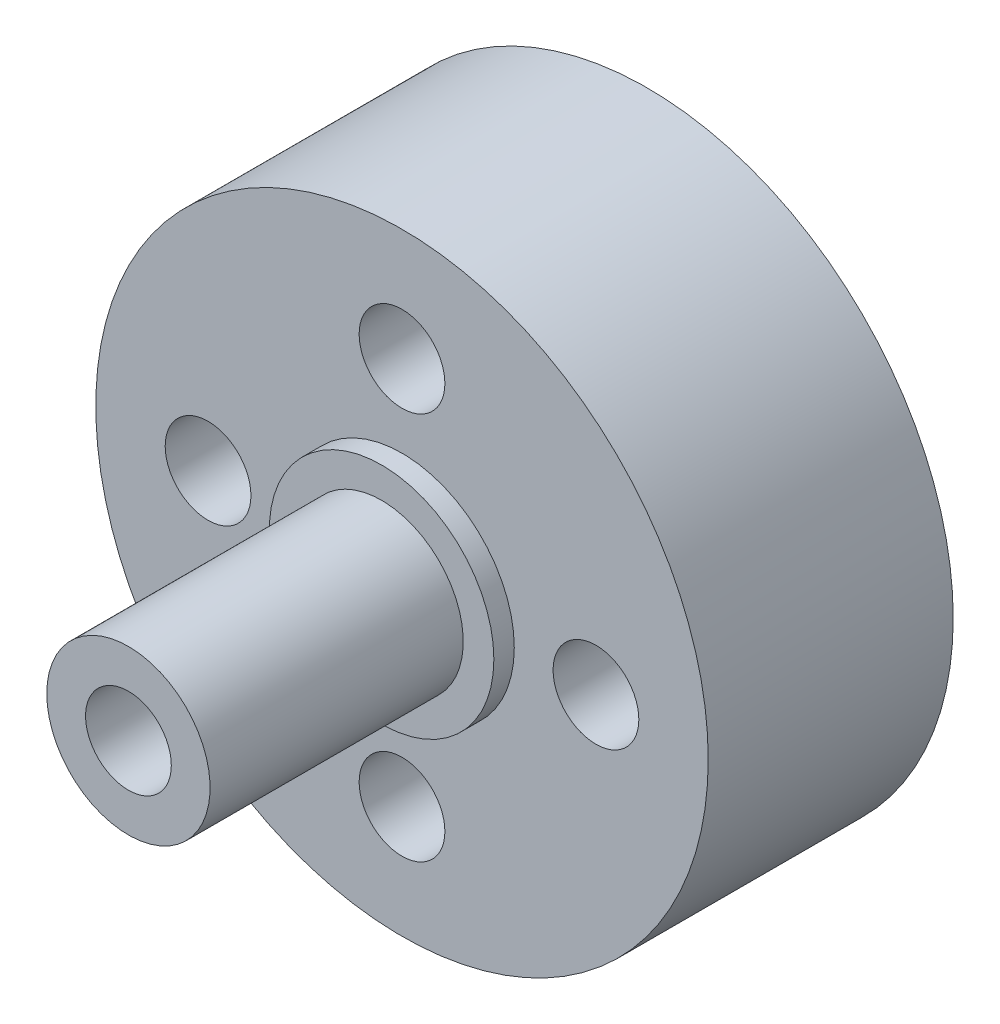
SolidWorks part; units mm, degrees
ref_plane "Спереди" through (0, 0, 0) normal (0, 0, 1) x (1, 0, 0)
ref_plane "Сверху" through (0, 0, 0) normal (0, 1, 0) x (1, 0, 0)
ref_plane "Справа" through (0, 0, 0) normal (1, 0, 0) x (0, 0, -1)
sketch "Эскиз1" plane through (0, 0, 0) normal (0, 0, 1) x (1, 0, 0)
  circle A0 centre (0, 0) radius 15
  dimension "D1" = 30
extrude "Бобышка-Вытянуть1" add sketch "Эскиз1" along normal blind 12
sketch "Эскиз2" plane through (0, 0, 12) normal (0, 0, 1) x (1, 0, 0)
  circle A0 centre (0, 0) radius 5.5
  dimension "D1" = 11
extrude "Бобышка-Вытянуть2" add sketch "Эскиз2" along normal blind 1
sketch "Эскиз3" plane through (0, 0, 13) normal (0, 0, 1) x (1, 0, 0)
  circle A0 centre (0, 0) radius 4
  dimension "D1" = 8
extrude "Бобышка-Вытянуть3" add sketch "Эскиз3" along normal blind 12.4
sketch "Эскиз4" plane through (0, 0, 0) normal (0, 0, -1) x (-1, 0, 0)
  line L0 (0, 15) -> (0, -15) construction
  line L1 (-15, 0) -> (15, 0) construction
  circle A0 centre (0, 0) radius 15 construction
  circle A1 centre (0, 0) radius 9.5 construction
  dimension "D1" = 19
hole_wizard "Отверстие обработанное метчиком M5x0.81" positions "Эскиз6" profile "Эскиз5" tap size "M5x0.8" standard "Ansi Metric" end condition through all
sketch "Эскиз6" plane through (0, 0, 0) normal (0, 0, -1) x (-1, 0, 0)
  line L0 (0, 15) -> (0, -15) construction
  line L1 (-15, 0) -> (15, 0) construction
  circle A0 centre (0, 0) radius 9.5 construction
  point P0 (0, 9.5)
  point P6 (9.5, 0)
  point P10 (-9.5, 0)
  point P12 (0, -9.5)
sketch "Эскиз5" plane through (0, 9.5, 0) normal (1, 0, 0) x (0, 1, 0)
  line L0 (0, 0) -> (0, 25.4)
  line L1 (0, 25.4) -> (2.1, 25.4)
  line L2 (2.1, 25.4) -> (2.1, 0)
  line L5 (2.1, 0) -> (0, 0)
  line L11 (0, -6.35) -> (0, 107.95) construction
  dimension "Диаметр проходного сверла" = 4.2
  dimension "Глубина проходного сверла" = 25.4
cosmetic thread "Отверстие резьбы1" parameters "D2"=5
cosmetic thread "Отверстие резьбы2" parameters "D2"=5
cosmetic thread "Отверстие резьбы3" parameters "D2"=5
cosmetic thread "Отверстие резьбы4" parameters "D2"=5
hole_wizard "Отверстие обработанное метчиком M5x0.82" positions "Эскиз8" profile "Эскиз7" tap size "M5x0.8" standard "Ansi Metric"
sketch "Эскиз8" plane through (0, 0, 25.4) normal (0, 0, 1) x (1, 0, 0)
  point P0 (0, 0)
sketch "Эскиз7" plane through (0, 0, 25.4) normal (1, 0, 0) x (0, -1, 0)
  line L0 (0, 0) -> (0, 15.2618)
  line L1 (0, 15.2618) -> (2.1, 14)
  line L2 (2.1, 14) -> (2.1, 0)
  line L5 (2.1, 0) -> (0, 0)
  line L10 (0, 15.2618) -> (-2.1, 14) construction
  line L11 (0, -6.35) -> (0, 107.95) construction
  dimension "Диаметр сверла" = 4.2
  dimension "Глубина сверла" = 14
  dimension "Угол заточки сверла" = 118
cosmetic thread "Отверстие резьбы5" parameters "D1"=10, "D2"=5
